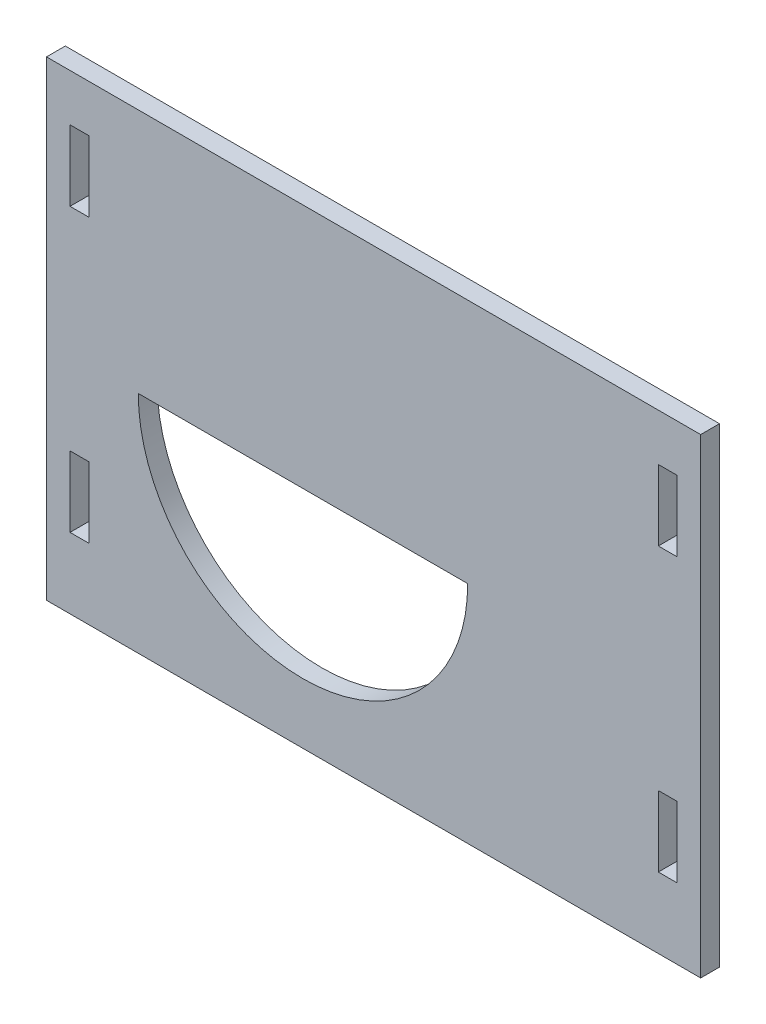
SolidWorks part; units mm, degrees
ref_plane "Front Plane" through (0, 0, 0) normal (0, 0, 1) x (1, 0, 0)
ref_plane "Top Plane" through (0, 0, 0) normal (0, 1, 0) x (1, 0, 0)
ref_plane "Right Plane" through (0, 0, 0) normal (1, 0, 0) x (0, 0, -1)
sketch "Sketch1" plane through (0, 0, 0) normal (0, 0, 1) x (1, 0, 0)
  line L0 (-35, -4.6786) -> (35, -4.6786)
  line L1 (-54.5, -52.5) -> (64.5, -52.5)
  line L3 (-54.5, 47.5) -> (64.5, 47.5)
  line L21 (0, 80.4433) -> (0, -75.6846) construction
  line L22 (45.5, 37.5) -> (49.5, 37.5) construction
  line L23 (45.5, 37.5) -> (45.5, 22.5) construction
  line L24 (45.5, 22.5) -> (49.5, 22.5) construction
  line L25 (49.5, 37.5) -> (49.5, 22.5) construction
  line L26 (-110.7456, 0) -> (128.9906, 0) construction
  line L27 (45.5, -22.5) -> (49.5, -22.5) construction
  line L28 (45.5, -37.5) -> (45.5, -22.5) construction
  line L29 (49.5, -37.5) -> (49.5, -22.5) construction
  line L30 (45.5, -37.5) -> (49.5, -37.5) construction
  line L31 (-45.5, -37.5) -> (-45.5, -22.5)
  line L32 (-45.5, -22.5) -> (-49.5, -22.5)
  line L33 (-49.5, -37.5) -> (-49.5, -22.5)
  line L34 (-45.5, -37.5) -> (-49.5, -37.5)
  line L35 (-45.5, 22.5) -> (-49.5, 22.5)
  line L36 (-45.5, 37.5) -> (-45.5, 22.5)
  line L37 (-49.5, 37.5) -> (-49.5, 22.5)
  line L38 (-45.5, 37.5) -> (-49.5, 37.5)
  line L42 (64.5, 47.5) -> (84.5, 47.5)
  line L51 (84.5, 47.5) -> (84.5, -52.5)
  line L52 (84.5, -52.5) -> (64.5, -52.5)
  line L53 (-54.5, 47.5) -> (-54.5, -52.5)
  line L54 (79.5, 37.5) -> (75.5, 37.5)
  line L55 (79.5, 37.5) -> (79.5, 22.5)
  line L56 (79.5, 22.5) -> (75.5, 22.5)
  line L57 (75.5, 37.5) -> (75.5, 22.5)
  line L58 (79.5, -22.5) -> (75.5, -22.5)
  line L59 (79.5, -22.5) -> (79.5, -37.5)
  line L60 (79.5, -37.5) -> (75.5, -37.5)
  line L61 (75.5, -22.5) -> (75.5, -37.5)
  arc A12 (-35, -4.6786) -> (35, -4.6786) centre (0, -4.6786) ccw
  point P0 (0, 0)
  dimension "D4" = 91
  dimension "D5" = 5
  dimension "D6" = 26
  dimension "D7" = 15
  dimension "D1" = 100
  dimension "D2" = 15
  dimension "D8" = 35
  dimension "D9" = 35
  dimension "D12" = 4
  dimension "D13" = 15
  dimension "D15" = 10
  dimension "D17" = 5
  dimension "D18" = 5
extrude "Boss-Extrude1" add sketch "Sketch1" along normal blind 4
